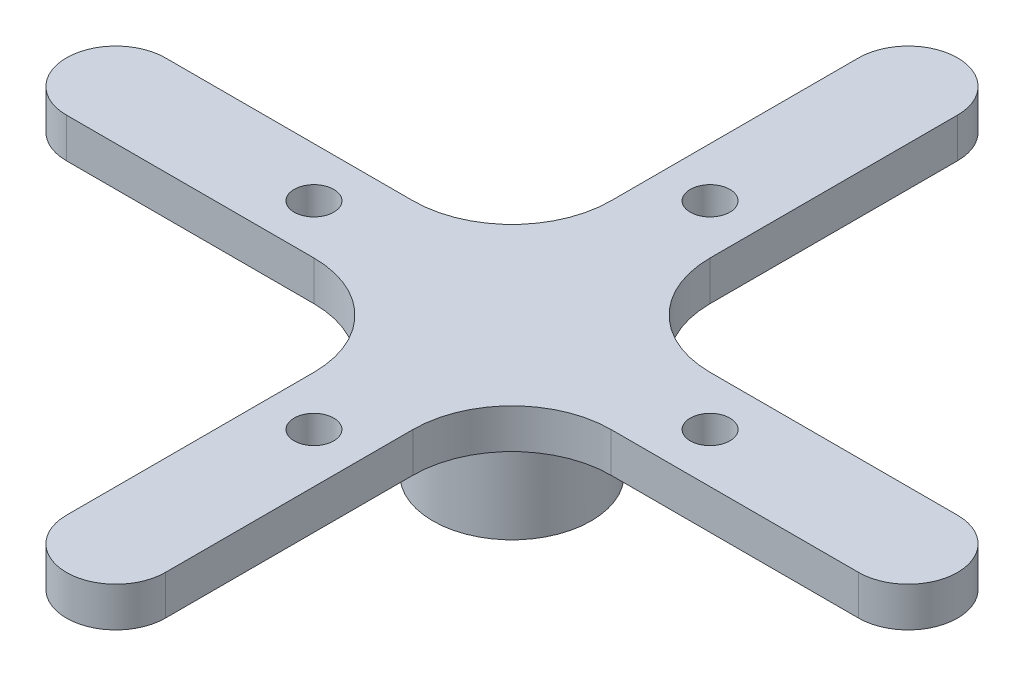
SolidWorks part; units mm, degrees
material "Nylon 101"
ref_plane "Front Plane" through (0, 0, 0) normal (0, 0, 1) x (1, 0, 0)
ref_plane "Top Plane" through (0, 0, 0) normal (0, 1, 0) x (1, 0, 0)
ref_plane "Right Plane" through (0, 0, 0) normal (1, 0, 0) x (0, 0, -1)
sketch "Sketch1" plane through (0, 0, 0) normal (0, 1, 0) x (1, 0, 0)
  line L2 (2.5, 20) -> (2.5, 7.5)
  line L4 (-2.5, 20) -> (-2.5, 7.5)
  line L7 (-20, 2.5) -> (-7.5, 2.5)
  line L9 (-20, -2.5) -> (-7.5, -2.5)
  line L14 (-2.5, -7.5) -> (-2.5, -20)
  line L16 (7.5, -2.5) -> (20, -2.5)
  line L18 (2.5, -7.5) -> (2.5, -20)
  line L19 (7.5, 2.5) -> (20, 2.5)
  arc A0 (-2.5, -7.5) -> (-7.5, -2.5) centre (-7.5, -7.5) ccw
  arc A1 (7.5, -2.5) -> (2.5, -7.5) centre (7.5, -7.5) ccw
  arc A2 (2.5, 7.5) -> (7.5, 2.5) centre (7.5, 7.5) ccw
  arc A3 (-7.5, 2.5) -> (-2.5, 7.5) centre (-7.5, 7.5) ccw
  arc A4 (-2.5, 20) -> (2.5, 20) centre (0, 20) cw
  arc A5 (20, 2.5) -> (20, -2.5) centre (20, 0) cw
  arc A6 (-2.5, -20) -> (2.5, -20) centre (0, -20) ccw
  arc A7 (-20, 2.5) -> (-20, -2.5) centre (-20, 0) ccw
  circle A8 centre (10, 0) radius 1
  circle A9 centre (-10, 0) radius 1
  circle A10 centre (0, 10) radius 1
  circle A11 centre (0, -10) radius 1
  point P0 (0, 0)
  point P6 (0, 0)
  point P20 (2.5, -2.5)
  dimension "D5" = 0
  dimension "D6" = 2
  dimension "D7" = 2
  dimension "D8" = 2
  dimension "D9" = 2
  dimension "D10" = 20
  dimension "D11" = 20
  dimension "D12" = 10
  dimension "D13" = 10
  dimension "D1" = 40
  dimension "D2" = 40
  dimension "D3" = 5
  dimension "D4" = 5
extrude "Boss-Extrude1" add sketch "Sketch1" along normal blind 2 contours L9 A0 L14 A6 L18 A1 L16 A5 L19 A2 L2 A4 L4 A3 L7 A7 | A8 | A11 | A10 | A9
sketch "Sketch2" plane through (0, 0, 0) normal (0, -1, 0) x (1, 0, 0)
  circle A0 centre (0, 0) radius 4
  circle A1 centre (0, 0) radius 2.95
  dimension "D1" = 8
  dimension "D2" = 5.9
extrude "Boss-Extrude2" add sketch "Sketch2" along normal blind 5
